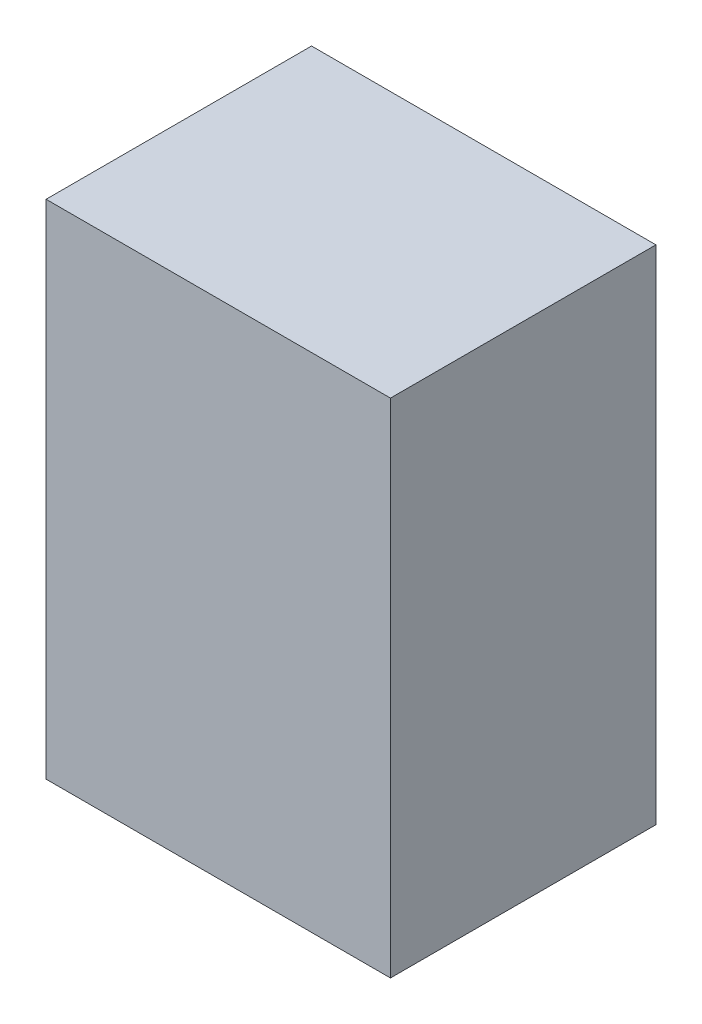
SolidWorks part; units mm, degrees
ref_plane "Front Plane" through (0, 0, 0) normal (0, 0, 1) x (1, 0, 0)
ref_plane "Top Plane" through (0, 0, 0) normal (0, 1, 0) x (1, 0, 0)
ref_plane "Right Plane" through (0, 0, 0) normal (1, 0, 0) x (0, 0, -1)
sketch "草图1" plane through (0, 0, 0) normal (0, 1, 0) x (1, 0, 0)
  line L1 (-2.4, -1.85) -> (2.4, -1.85)
  line L2 (-2.4, -1.85) -> (-2.4, 1.85)
  line L3 (-2.4, 1.85) -> (2.4, 1.85)
  line L4 (2.4, -1.85) -> (2.4, 1.85)
  line L5 (-2.4, -1.85) -> (2.4, 1.85) construction
  line L6 (-2.4, 1.85) -> (2.4, -1.85) construction
  point P0 (0, 0)
  dimension "D1" = 4.8
  dimension "D2" = 3.7
extrude "凸台-拉伸1" add sketch "草图1" along normal blind 7
